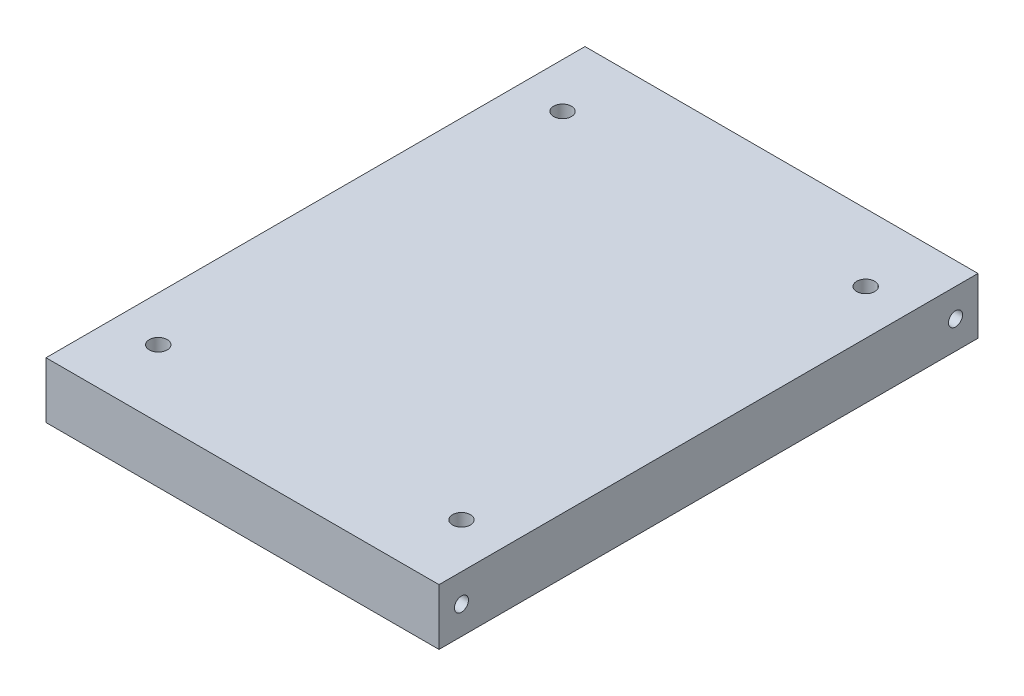
SolidWorks part; units mm, degrees
ref_plane "Front Plane" through (0, 0, 0) normal (0, 0, 1) x (1, 0, 0)
ref_plane "Top Plane" through (0, 0, 0) normal (0, 1, 0) x (1, 0, 0)
ref_plane "Right Plane" through (0, 0, 0) normal (1, 0, 0) x (0, 0, -1)
sketch "Sketch1" plane through (0, 316.5667, 0) normal (0, -1, 0) x (1, 0, 0)
  line L0 (-27, 59.5843) -> (27, -12.4157) construction
  line L2 (27, 59.5843) -> (-27, -12.4157) construction
  line L3 (-35, -24.4157) -> (35, -24.4157)
  line L4 (-35, -24.4157) -> (-35, 71.5843)
  line L5 (-35, 71.5843) -> (35, 71.5843)
  line L6 (35, -24.4157) -> (35, 71.5843)
  line L7 (-35, -24.4157) -> (35, 71.5843) construction
  line L8 (-35, 71.5843) -> (35, -24.4157) construction
  line L10 (-20.8, 71.5843) -> (20.8, 71.5843) construction
  circle A0 centre (-27, 59.5843) radius 1.6
  circle A1 centre (27, 59.5843) radius 1.6
  circle A2 centre (-27, -12.4157) radius 1.6
  circle A3 centre (27, -12.4157) radius 1.6
  point P8 (0, 23.5843)
  point P22 (0, 0)
  dimension "D1" = 3.2
  dimension "D2" = 70
extrude "Boss-Extrude1" add sketch "Sketch1" along normal blind 10
sketch "Sketch2" plane through (-35, 0, 0) normal (-1, 0, 0) x (0, 0, 1)
  line L0 (-24.4157, 311.5667) -> (71.5843, 311.5667) construction
  line L1 (-24.4157, 306.5667) -> (-24.4157, 316.5667) construction
  line L2 (71.5843, 306.5667) -> (71.5843, 316.5667) construction
  circle A0 centre (-20.4157, 311.5667) radius 1.25
  circle A1 centre (67.5843, 311.5667) radius 1.25
  dimension "D1" = 2.5
  dimension "D2" = 4
  dimension "D3" = 4
extrude "Cut-Extrude1" cut sketch "Sketch2" against normal blind 10
mirror "Mirror1" about plane through (0, 0, 0) normal (1, 0, 0) of "Cut-Extrude1"
